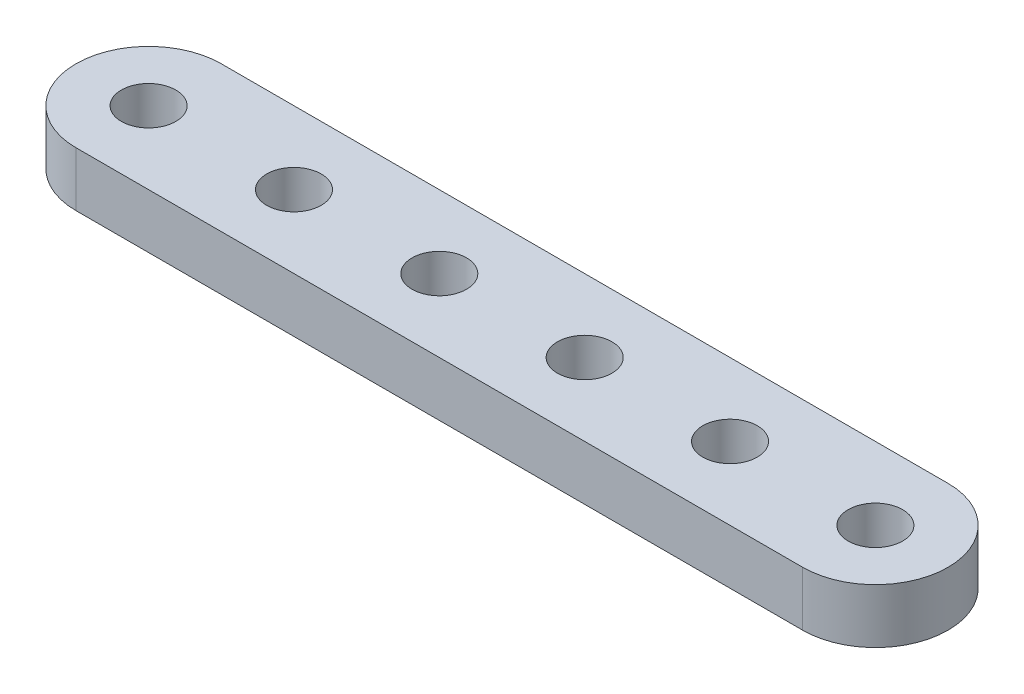
SolidWorks part; units mm, degrees
ref_plane "Front Plane" through (0, 0, 0) normal (0, 0, 1) x (1, 0, 0)
ref_plane "Top Plane" through (0, 0, 0) normal (0, 1, 0) x (1, 0, 0)
ref_plane "Right Plane" through (0, 0, 0) normal (1, 0, 0) x (0, 0, -1)
sketch "Sketch2" plane through (0, 0, 0) normal (0, 1, 0) x (1, 0, 0)
  line L0 (0, 0) -> (40, 0) construction
  line L1 (0, 4) -> (40, 4)
  line L2 (0, -4) -> (40, -4)
  arc A0 (0, 4) -> (0, -4) centre (0, 0) ccw
  arc A1 (40, -4) -> (40, 4) centre (40, 0) ccw
  circle A2 centre (0, 0) radius 1.5
  circle A3 centre (8, 0) radius 1.5
  circle A4 centre (16, 0) radius 1.5
  circle A5 centre (24, 0) radius 1.5
  circle A6 centre (32, 0) radius 1.5
  circle A7 centre (40, 0) radius 1.5
  point P3 (20, 0)
  point P10 (0, 0)
  dimension "D1" = 3
  dimension "D2" = 8
  dimension "D3" = 40
  dimension "D5" = 8
  dimension "D4" = 6
extrude "Boss-Extrude2" add sketch "Sketch2" along normal blind 3
